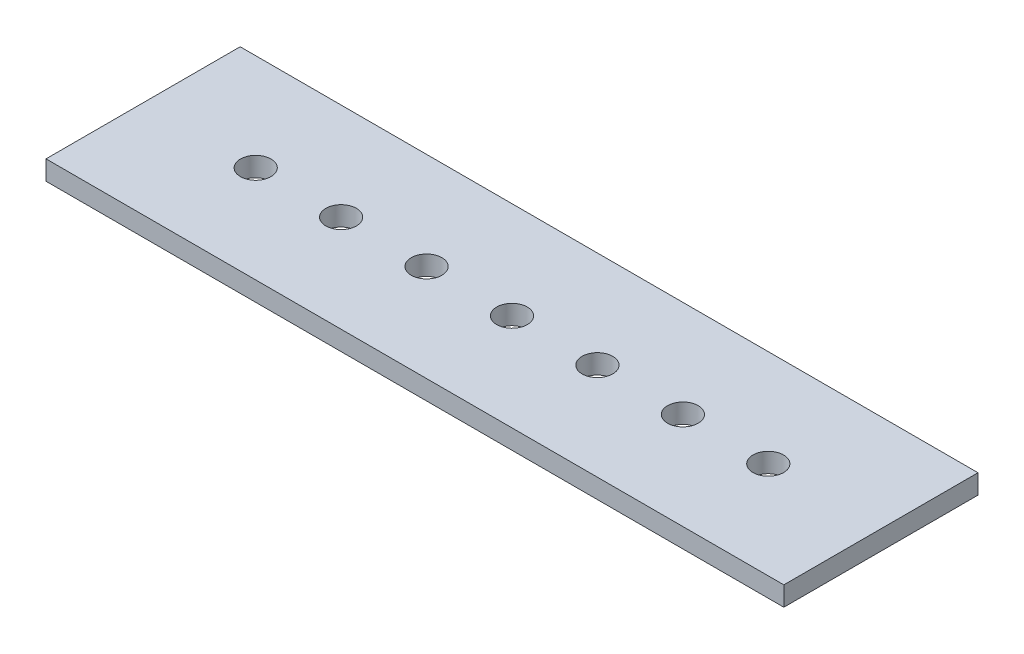
SolidWorks part; units mm, degrees
ref_plane "Front Plane" through (0, 0, 0) normal (0, 0, 1) x (1, 0, 0)
ref_plane "Top Plane" through (0, 0, 0) normal (0, 1, 0) x (1, 0, 0)
ref_plane "Right Plane" through (0, 0, 0) normal (1, 0, 0) x (0, 0, -1)
sketch "Sketch1" plane through (0, 0, 0) normal (0, 1, 0) x (1, 0, 0)
  line L1 (0, 0) -> (120.65, 0)
  line L2 (0, 0) -> (0, 31.75)
  line L3 (0, 31.75) -> (120.65, 31.75)
  line L4 (120.65, 0) -> (120.65, 31.75)
  dimension "D1" = 120.65
  dimension "D2" = 31.75
extrude "Boss-Extrude1" add sketch "Sketch1" along normal blind 3.175
sketch "Sketch2" plane through (0, 3.175, 0) normal (0, 1, 0) x (1, 0, 0)
  line L1 (120.65, 31.75) -> (0, 31.75) construction
  circle A0 centre (60.325, 15.875) radius 2.5
  point P2 (60.325, 31.75)
  dimension "D1" = 5
  dimension "D3" = 15.875
extrude "Cut-Extrude1" cut sketch "Sketch2" against normal blind 5.08
pattern_linear "LPattern2" count 4 spacing 13.97 along (1, 0, 0) count 4 spacing 13.97 along (-1, 0, 0) of "Cut-Extrude1"
